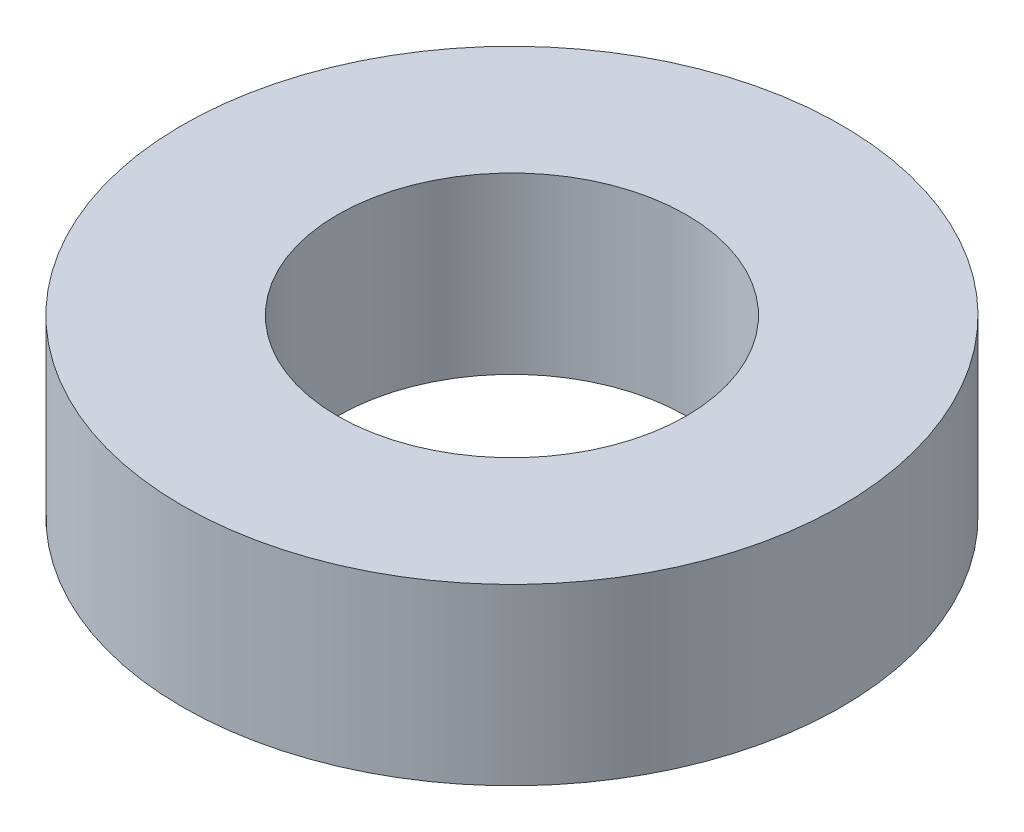
SolidWorks part; units mm, degrees
ref_plane "Plan de face" through (0, 0, 0) normal (0, 0, 1) x (1, 0, 0)
ref_plane "Plan de dessus" through (0, 0, 0) normal (0, 1, 0) x (1, 0, 0)
ref_plane "Plan de droite" through (0, 0, 0) normal (1, 0, 0) x (0, 0, -1)
sketch "Esquisse1" plane through (0, 0, 0) normal (0, 1, 0) x (1, 0, 0)
  circle A0 centre (0, 0) radius 9.45
  dimension "D1" = 18.9
extrude "Boss.-Extru.1" add sketch "Esquisse1" along normal blind 5
sketch "Esquisse2" plane through (0, 0, 0) normal (0, -1, 0) x (1, 0, 0)
  circle A0 centre (0, 0) radius 5
  dimension "D1" = 10
extrude "Enlèv. mat.-Extru.1" cut sketch "Esquisse2" against normal blind 7.7
